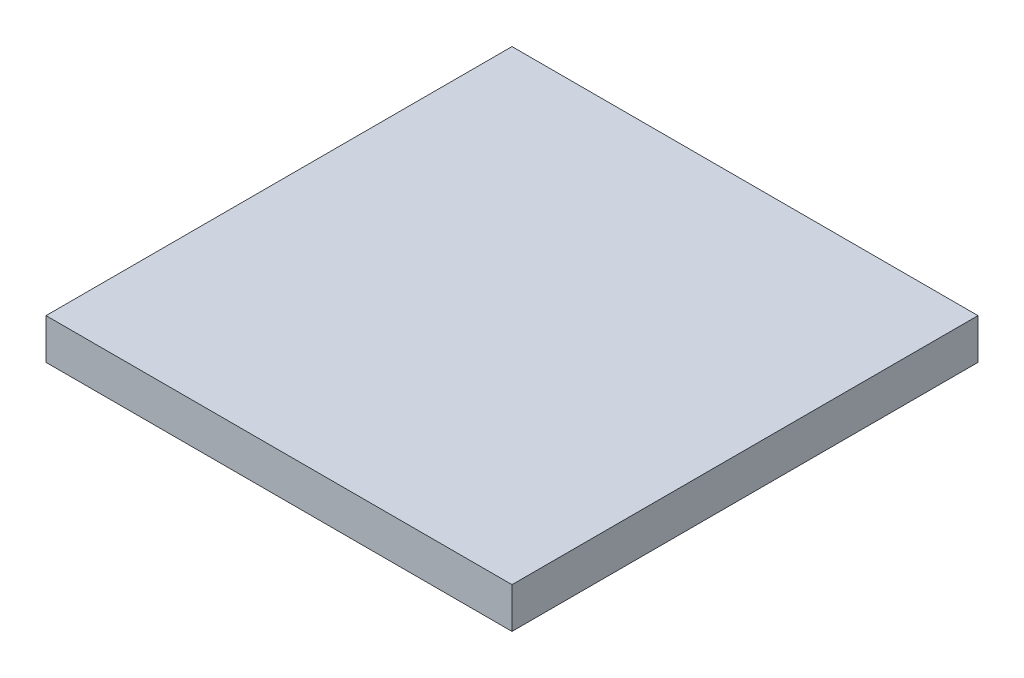
SolidWorks part; units mm, degrees
ref_plane "Front Plane" through (0, 0, 0) normal (0, 0, 1) x (1, 0, 0)
ref_plane "Top Plane" through (0, 0, 0) normal (0, 1, 0) x (1, 0, 0)
ref_plane "Right Plane" through (0, 0, 0) normal (1, 0, 0) x (0, 0, -1)
sketch "Sketch1" plane through (0, 0, 0) normal (0, 1, 0) x (1, 0, 0)
  line L1 (-57.5, -57.5) -> (57.5, -57.5)
  line L2 (-57.5, -57.5) -> (-57.5, 57.5)
  line L3 (-57.5, 57.5) -> (57.5, 57.5)
  line L4 (57.5, -57.5) -> (57.5, 57.5)
  line L5 (-57.5, -57.5) -> (57.5, 57.5) construction
  line L6 (-57.5, 57.5) -> (57.5, -57.5) construction
  point P0 (0, 0)
  dimension "D1" = 115
  dimension "D2" = 115
extrude "Boss-Extrude1" add sketch "Sketch1" along normal blind 10
